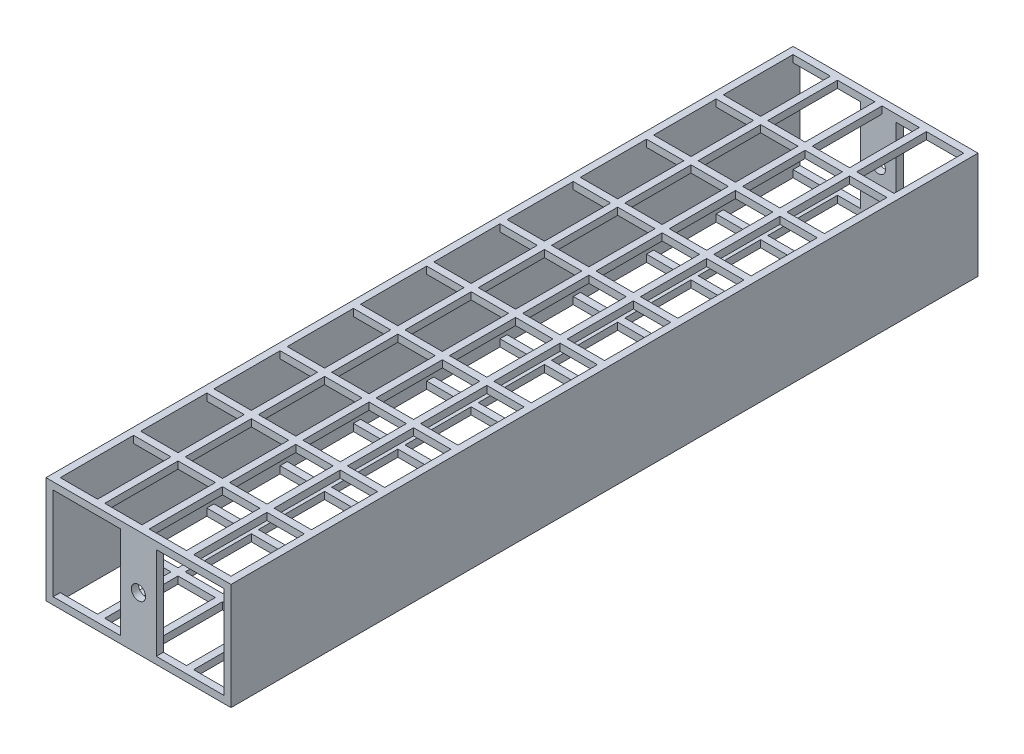
SolidWorks part; units mm, degrees
material "1023 Chapa de acero al carbono (SS)"
ref_plane "Alzado" through (0, 0, 0) normal (0, 0, 1) x (1, 0, 0)
ref_plane "Planta" through (0, 0, 0) normal (0, 1, 0) x (1, 0, 0)
ref_plane "Vista lateral" through (0, 0, 0) normal (1, 0, 0) x (0, 0, -1)
sketch "Croquis2" plane through (0, 0, 0) normal (0, 1, 0) x (1, 0, 0)
  line L0 (-1, 3.5412) -> (-1, -15.0588)
  line L1 (-26, 108.5256) -> (26, 108.5256)
  line L2 (-26, 108.5256) -> (-26, -101.4744)
  line L3 (-26, -101.4744) -> (26, -101.4744)
  line L4 (26, 108.5256) -> (26, -101.4744)
  line L5 (-1, 24.1412) -> (-1, 5.5412)
  line L6 (-24, 65.3412) -> (-24, 46.7412)
  line L7 (-24, 106.5256) -> (-13.5, 106.5256)
  line L8 (-1, 44.7412) -> (-1, 26.1412)
  line L9 (-1, 106.5256) -> (-1, 86.9256)
  line L10 (-1, -101.4744) -> (-2.4262, -101.4744)
  line L11 (1, 106.5256) -> (1, -99.4744)
  line L12 (-24, 106.5256) -> (-24, 86.9256)
  line L13 (-1, 84.9256) -> (-1, 67.3412)
  line L14 (-24, 106.5256) -> (-13.5, 106.5256)
  line L15 (-24, 106.5256) -> (-24, 86.9256)
  line L16 (-24, -99.4744) -> (-13.5, -99.4744)
  line L17 (24, 106.5256) -> (24, -99.4744)
  line L18 (-24, 24.1412) -> (-24, 5.5412)
  line L19 (-24, 44.7412) -> (-24, 26.1412)
  line L20 (1, 106.5256) -> (24, 106.5256)
  line L21 (1, -99.4744) -> (24, -99.4744)
  line L22 (-1, 106.5256) -> (-1, 86.9256)
  line L23 (-4.2108, 67.3412) -> (-1, 67.3412)
  line L24 (-1, 65.3412) -> (-1, 46.7412)
  line L25 (-24, -17.0588) -> (-24, -35.6588)
  line L26 (-24, 3.5412) -> (-24, -15.0588)
  line L27 (-1, -58.2588) -> (-1, -76.8588)
  line L28 (-24, -78.8588) -> (-24, -99.4744)
  line L29 (-24, 67.3412) -> (-13.5, 67.3412)
  line L30 (-24, 86.9256) -> (-13.5, 86.9256)
  line L31 (-1, -78.8588) -> (-1, -99.4744)
  line L32 (-24, 84.9256) -> (-13.5, 84.9256)
  line L33 (-12.5, 108.5256) -> (-13.5, 108.5256)
  line L34 (-24, 65.3412) -> (-13.5, 65.3412)
  line L35 (-24, 46.7412) -> (-13.5, 46.7412)
  line L36 (-24, 44.7412) -> (-13.5, 44.7412)
  line L37 (-24, 5.5412) -> (-13.5, 5.5412)
  line L38 (-24, 3.5412) -> (-13.5, 3.5412)
  line L39 (-24, 26.1412) -> (-13.5, 26.1412)
  line L40 (-24, 24.1412) -> (-13.5, 24.1412)
  line L41 (-24, -15.0588) -> (-13.5, -15.0588)
  line L42 (-24, -17.0588) -> (-13.5, -17.0588)
  line L43 (-24, -35.6588) -> (-13.5, -35.6588)
  line L44 (-24, -37.6588) -> (-1, -37.6588)
  line L45 (-24, -76.8588) -> (-13.5, -76.8588)
  line L46 (-24, -78.8588) -> (-13.5, -78.8588)
  line L47 (-24, -56.2588) -> (-13.5, -56.2588)
  line L48 (-24, -58.2588) -> (-13.5, -58.2588)
  line L49 (-24, -37.6588) -> (-24, -56.2588)
  line L50 (-1, -37.6588) -> (-1, -56.2588)
  line L51 (-1, -17.0588) -> (-1, -35.6588)
  line L52 (-24, 84.9256) -> (-24, 67.3412)
  line L53 (-24, -58.2588) -> (-24, -76.8588)
  line L54 (1, 44.7412) -> (11.5, 44.7412)
  line L55 (11.5, 106.5256) -> (11.5, 86.9256)
  line L56 (13.5, -17.0588) -> (13.5, -35.6588)
  line L57 (24, 24.1412) -> (24, 5.5412)
  line L58 (-13.5, 106.5256) -> (-13.5, 86.9256)
  line L59 (-12.5, 108.5256) -> (-11.5, 108.5256)
  line L60 (-11.5, 106.5256) -> (-11.5, 86.9256)
  line L61 (-11.5, -99.4744) -> (-1, -99.4744)
  line L62 (-11.5, -78.8588) -> (-1, -78.8588)
  line L63 (-11.5, -76.8588) -> (-1, -76.8588)
  line L64 (-13.5, -78.8588) -> (-13.5, -99.4744)
  line L65 (-11.5, -78.8588) -> (-11.5, -99.4744)
  line L66 (-11.5, -58.2588) -> (-11.5, -76.8588)
  line L67 (-13.5, -58.2588) -> (-13.5, -76.8588)
  line L68 (-11.5, -58.2588) -> (-1, -58.2588)
  line L69 (-11.5, -56.2588) -> (-1, -56.2588)
  line L70 (-11.5, -37.6588) -> (-11.5, -56.2588)
  line L71 (-13.5, -37.6588) -> (-13.5, -56.2588)
  line L72 (-11.5, -35.6588) -> (-1, -35.6588)
  line L73 (-11.5, -17.0588) -> (-1, -17.0588)
  line L74 (-11.5, -15.0588) -> (-1, -15.0588)
  line L75 (-13.5, -17.0588) -> (-13.5, -35.6588)
  line L76 (-11.5, -17.0588) -> (-11.5, -35.6588)
  line L77 (-11.5, 3.5412) -> (-1, 3.5412)
  line L78 (-11.5, 5.5412) -> (-1, 5.5412)
  line L79 (-11.5, 3.5412) -> (-11.5, -15.0588)
  line L80 (-13.5, 3.5412) -> (-13.5, -15.0588)
  line L81 (-11.5, 24.1412) -> (-1, 24.1412)
  line L82 (-11.5, 26.1412) -> (-1, 26.1412)
  line L83 (-13.5, 24.1412) -> (-13.5, 5.5412)
  line L84 (-11.5, 24.1412) -> (-11.5, 5.5412)
  line L85 (-11.5, 44.7412) -> (-1, 44.7412)
  line L86 (-11.5, 46.7412) -> (-1, 46.7412)
  line L87 (-13.5, 44.7412) -> (-13.5, 26.1412)
  line L88 (-11.5, 44.7412) -> (-11.5, 26.1412)
  line L89 (-11.5, 65.3412) -> (-1, 65.3412)
  line L90 (-11.5, 67.3412) -> (-4.2108, 67.3412)
  line L91 (-13.5, 65.3412) -> (-13.5, 46.7412)
  line L92 (-11.5, 65.3412) -> (-11.5, 46.7412)
  line L93 (-11.5, 84.9256) -> (-1, 84.9256)
  line L94 (-11.5, 86.9256) -> (-1, 86.9256)
  line L95 (-13.5, 84.9256) -> (-13.5, 67.3412)
  line L96 (-11.5, 84.9256) -> (-11.5, 67.3412)
  line L97 (-11.5, 106.5256) -> (-1, 106.5256)
  line L98 (-11.5, 106.5256) -> (-1, 106.5256)
  line L99 (24, 44.7412) -> (24, 26.1412)
  line L100 (1, 84.9256) -> (11.5, 84.9256)
  line L101 (13.5, -58.2588) -> (13.5, -76.8588)
  line L102 (13.5, 106.5256) -> (24, 106.5256)
  line L103 (1, 24.1412) -> (1, 5.5412)
  line L104 (1, 65.3412) -> (11.5, 65.3412)
  line L105 (1, 24.1412) -> (11.5, 24.1412)
  line L106 (13.5, -78.8588) -> (24, -78.8588)
  line L107 (13.5, -78.8588) -> (13.5, -99.4744)
  line L108 (13.5, 65.3412) -> (13.5, 46.7412)
  line L109 (1, 44.7412) -> (1, 26.1412)
  line L110 (1, 5.5412) -> (11.5, 5.5412)
  line L111 (1, -35.6588) -> (11.5, -35.6588)
  line L112 (1, -76.8588) -> (11.5, -76.8588)
  line L113 (11.5, -58.2588) -> (11.5, -76.8588)
  line L114 (13.5, 24.1412) -> (13.5, 5.5412)
  line L115 (11.5, 65.3412) -> (11.5, 46.7412)
  line L116 (1, 106.5256) -> (1, 86.9256)
  line L117 (24, -78.8588) -> (24, -99.4744)
  line L118 (12.5, 108.5256) -> (13.5, 108.5256)
  line L119 (13.5, 44.7412) -> (24, 44.7412)
  line L120 (-1, 108.5256) -> (-1, -101.4744)
  line L121 (1, -17.0588) -> (1, -35.6588)
  line L122 (1, 3.5412) -> (11.5, 3.5412)
  line L123 (1, -17.0588) -> (11.5, -17.0588)
  line L124 (24, -37.6588) -> (24, -56.2588)
  line L125 (13.5, -58.2588) -> (24, -58.2588)
  line L126 (13.5, 84.9256) -> (13.5, 67.3412)
  line L127 (1, 106.5256) -> (11.5, 106.5256)
  line L128 (24, 106.5256) -> (24, 86.9256)
  line L129 (1, -58.2588) -> (1, -76.8588)
  line L130 (13.5, 3.5412) -> (24, 3.5412)
  line L131 (13.5, 65.3412) -> (24, 65.3412)
  line L132 (24, 106.5256) -> (24, 86.9256)
  line L133 (1, -15.0588) -> (11.5, -15.0588)
  line L134 (13.5, -56.2588) -> (24, -56.2588)
  line L135 (11.5, -17.0588) -> (11.5, -35.6588)
  line L136 (11.5, 84.9256) -> (11.5, 67.3412)
  line L137 (1, 106.5256) -> (1, 86.9256)
  line L138 (20.7892, 67.3412) -> (24, 67.3412)
  line L139 (24, -58.2588) -> (24, -76.8588)
  line L140 (1, -37.6588) -> (24, -37.6588)
  line L141 (13.5, 106.5256) -> (13.5, 86.9256)
  line L142 (13.5, 84.9256) -> (24, 84.9256)
  line L143 (24, 3.5412) -> (24, -15.0588)
  line L144 (12.5, 108.5256) -> (11.5, 108.5256)
  line L145 (1, 26.1412) -> (11.5, 26.1412)
  line L146 (11.5, -78.8588) -> (11.5, -99.4744)
  line L147 (13.5, -35.6588) -> (24, -35.6588)
  line L148 (13.5, 24.1412) -> (24, 24.1412)
  line L149 (26, 106.5256) -> (26, -99.4744)
  line L150 (13.5, -17.0588) -> (24, -17.0588)
  line L151 (11.5, 44.7412) -> (11.5, 26.1412)
  line L152 (13.5, 44.7412) -> (13.5, 26.1412)
  line L153 (24, -101.4744) -> (22.5738, -101.4744)
  line L154 (24, 65.3412) -> (24, 46.7412)
  line L155 (1, 86.9256) -> (11.5, 86.9256)
  line L156 (1, -56.2588) -> (11.5, -56.2588)
  line L157 (13.5, -37.6588) -> (13.5, -56.2588)
  line L158 (11.5, -37.6588) -> (11.5, -56.2588)
  line L159 (11.5, 3.5412) -> (11.5, -15.0588)
  line L160 (1, 46.7412) -> (11.5, 46.7412)
  line L161 (1, 84.9256) -> (1, 67.3412)
  line L162 (13.5, -15.0588) -> (24, -15.0588)
  line L163 (13.5, 106.5256) -> (24, 106.5256)
  line L164 (1, 65.3412) -> (1, 46.7412)
  line L165 (1, 67.3412) -> (11.5, 67.3412)
  line L166 (13.5, -76.8588) -> (24, -76.8588)
  line L167 (13.5, 86.9256) -> (24, 86.9256)
  line L168 (1, -99.4744) -> (11.5, -99.4744)
  line L169 (1, 3.5412) -> (1, -15.0588)
  line L170 (1, -37.6588) -> (1, -56.2588)
  line L171 (13.5, -99.4744) -> (24, -99.4744)
  line L172 (13.5, 46.7412) -> (24, 46.7412)
  line L173 (24, 84.9256) -> (24, 67.3412)
  line L174 (1, -78.8588) -> (11.5, -78.8588)
  line L175 (1, -58.2588) -> (11.5, -58.2588)
  line L176 (13.5, 3.5412) -> (13.5, -15.0588)
  line L177 (13.5, 26.1412) -> (24, 26.1412)
  line L178 (13.5, 67.3412) -> (20.7892, 67.3412)
  line L179 (1, 106.5256) -> (11.5, 106.5256)
  line L180 (1, -78.8588) -> (1, -99.4744)
  line L181 (24, -17.0588) -> (24, -35.6588)
  line L182 (13.5, 5.5412) -> (24, 5.5412)
  line L183 (11.5, 24.1412) -> (11.5, 5.5412)
  point P0 (0, 0)
  point P8 (0, 0)
  point P13 (0, 0)
  point P24 (25, 0)
  point P105 (25, 0)
  point P110 (25, 0)
  dimension "D1" = 52
  dimension "D2" = 210
  dimension "D3" = 2
  dimension "D4" = 206
  dimension "D5" = 48
  dimension "D6" = 0
  dimension "D7" = 0
  dimension "D8" = 2
  dimension "D9" = 0
  dimension "D10" = 2
  dimension "D12" = 2
  dimension "D14" = 2
  dimension "D15" = 0
  dimension "D16" = 0
extrude "Saliente-Extruir2" add sketch "Croquis2" along normal blind 30
sketch "Croquis3" plane through (0, 0, -108.5256) normal (0, 0, -1) x (-1, 0, 0)
  line L0 (-26, 30) -> (-26, 0) construction
  line L1 (-24, 28) -> (24, 28)
  line L2 (-24, 28) -> (-24, 2)
  line L3 (-24, 2) -> (24, 2)
  line L4 (24, 28) -> (24, 2)
  line L5 (26, 0) -> (-26, 0) construction
  line L6 (26, 30) -> (26, 0) construction
  line L7 (26, 30) -> (-26, 30) construction
  dimension "D1" = 2
  dimension "D2" = 2
  dimension "D3" = 2
  dimension "D4" = 2
extrude "Cortar-Extruir1" cut sketch "Croquis3" against normal blind 219
sketch "Croquis4" plane through (0, 0, 101.4744) normal (0, 0, 1) x (1, 0, 0)
  line L0 (-26, 30) -> (26, 30) construction
  line L1 (-5, 30) -> (5, 30)
  line L2 (-5, 30) -> (-5, 0)
  line L3 (-5, 0) -> (5, 0)
  line L4 (5, 30) -> (5, 0)
  line L5 (-26, 0) -> (26, 0) construction
  dimension "D1" = 10
  dimension "D2" = 5
extrude "Saliente-Extruir3" add sketch "Croquis4" against normal blind 2
sketch "Croquis5" plane through (0, 0, 101.4744) normal (0, 0, 1) x (1, 0, 0)
  line L0 (-5, 28) -> (5, 2)
  circle A0 centre (0, 15) radius 2
extrude "Cortar-Extruir2" cut sketch "Croquis5" against normal blind 2 contours L0 A0 | L0 A0
sketch "Croquis6" plane through (0, 0, -108.5256) normal (0, 0, -1) x (-1, 0, 0)
  line L1 (-5, 28) -> (5, 28)
  line L2 (-5, 28) -> (-5, 2)
  line L3 (-5, 2) -> (5, 2)
  line L4 (5, 28) -> (5, 2)
extrude "Saliente-Extruir4" add sketch "Croquis6" against normal blind 2
sketch "Croquis7" plane through (0, 0, -108.5256) normal (0, 0, -1) x (-1, 0, 0)
  line L0 (-5, 28) -> (5, 2)
  circle A0 centre (0, 15) radius 2
extrude "Cortar-Extruir3" cut sketch "Croquis7" against normal blind 2 contours L0 A0 | L0 A0
